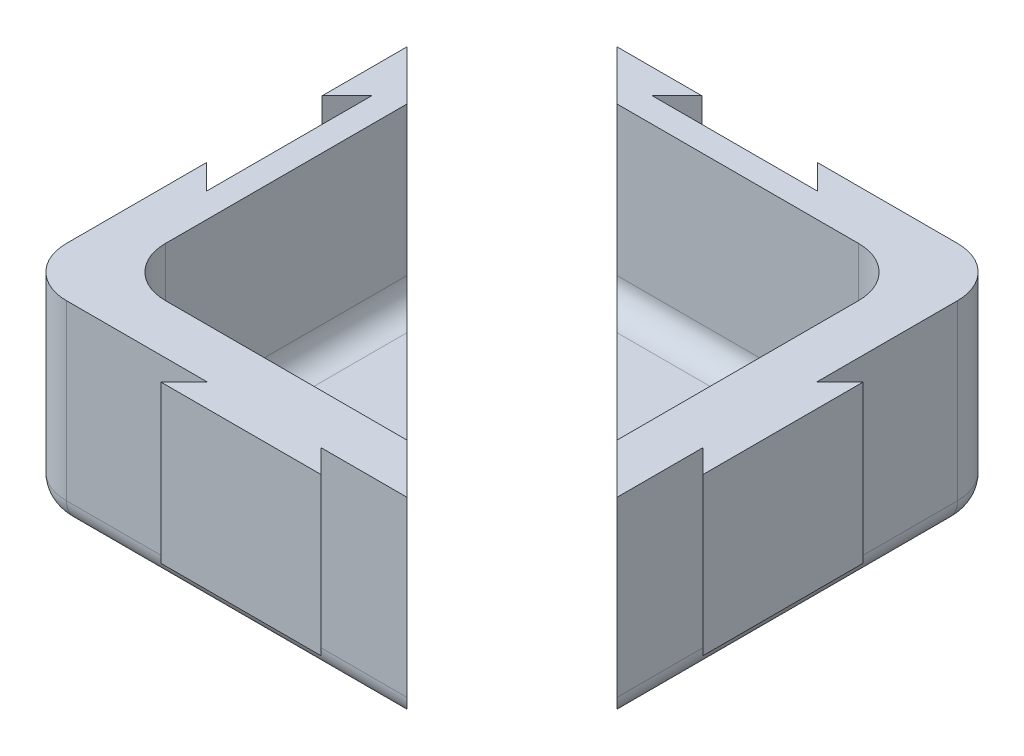
SolidWorks part; units mm, degrees
ref_plane "Front Plane" through (0, 0, 0) normal (0, 0, 1) x (1, 0, 0)
ref_plane "Top Plane" through (0, 0, 0) normal (0, 1, 0) x (1, 0, 0)
ref_plane "Right Plane" through (0, 0, 0) normal (1, 0, 0) x (0, 0, -1)
sketch "Sketch1" plane through (0, 0, 0) normal (0, 1, 0) x (1, 0, 0)
  line L1 (-50, 50) -> (50, 50)
  line L2 (-50, 50) -> (-50, -50)
  line L3 (-50, -50) -> (50, -50)
  line L4 (50, 50) -> (50, -50)
  line L5 (-50, 50) -> (50, -50) construction
  line L6 (-50, -50) -> (50, 50) construction
  point P0 (0, 0)
  dimension "D1" = 100
  dimension "D2" = 100
extrude "Boss-Extrude1" add sketch "Sketch1" along normal blind 40
shell "Shell1" thickness 10
sketch "Sketch2" plane through (0, 40, 0) normal (0, 1, 0) x (1, 0, 0)
  line L0 (-50, 45) -> (50, 45) construction
  line L1 (-50, 50) -> (-50, -50) construction
  line L2 (50, -50) -> (50, 50) construction
  line L3 (40, 40) -> (-40, 40) construction
  line L4 (-11.6667, 50) -> (-16.6667, 45)
  line L5 (50, 50) -> (-50, 50) construction
  line L6 (-16.6667, 45) -> (16.6667, 45)
  line L7 (16.6667, 45) -> (11.6667, 50)
  line L8 (-11.6667, 50) -> (11.6667, 50)
  point P14 (0, 45)
  dimension "D1" = 5
  dimension "D2" = 45
  dimension "D3" = 100
  dimension "D4" = 33.3333
extrude "Cut-Extrude1" cut sketch "Sketch2" against normal blind 32
sketch "Sketch3" plane through (0, 40, 0) normal (0, 1, 0) x (1, 0, 0)
  line L0 (-11.6667, -50) -> (-16.6667, -55) construction
  line L1 (-50, -50) -> (50, -50) construction
  line L2 (-16.6667, -55) -> (16.6667, -55) construction
  line L3 (16.6667, -55) -> (11.6667, -50) construction
  line L4 (11.6667, -50) -> (-11.6667, -50) construction
  line L5 (-50, -45) -> (50, -45) construction
  line L6 (-50, 50) -> (-50, -50) construction
  line L7 (50, -50) -> (50, 50) construction
  line L8 (-40, -40) -> (40, -40) construction
  line L9 (-11.4545, -50) -> (-16.1545, -54.7)
  line L10 (-11.4545, -50) -> (11.4545, -50)
  line L11 (-16.1545, -54.7) -> (16.1545, -54.7)
  line L12 (-11.5606, -50.1061) -> (-16.5606, -55.1061) construction
  line L14 (16.1545, -54.7) -> (11.4545, -50)
  point P4 (0, -50)
  dimension "D3" = 100
  dimension "D4" = 33.3333
  dimension "D1" = 45
  dimension "D2" = 5
  dimension "D5" = 5
  dimension "D7" = 0.3
  dimension "D8" = 0.15
  dimension "D6" = 0.15
extrude "Boss-Extrude2" add sketch "Sketch3" against normal blind 31.7
sketch "Sketch4" plane through (0, 40, 0) normal (0, 1, 0) x (1, 0, 0)
  line L0 (-45, 50) -> (-45, -50) construction
  line L1 (-11.6667, 50) -> (-50, 50) construction
  line L2 (-50, -50) -> (-11.4545, -50) construction
  line L3 (-40, 40) -> (-40, -40) construction
  line L4 (-45, 16.6667) -> (-45, -16.6667)
  line L5 (-45, -16.6667) -> (-50, -11.6667)
  line L6 (-50, 50) -> (-50, -50) construction
  line L7 (-50, -11.6667) -> (-50, 11.6667)
  line L8 (-50, 11.6667) -> (-45, 16.6667)
  point P14 (-45, 0)
  dimension "D1" = 5
  dimension "D2" = 45
  dimension "D3" = 33.3333
extrude "Cut-Extrude2" cut sketch "Sketch4" against normal blind 32
sketch "Sketch5" plane through (0, 40, 0) normal (0, 1, 0) x (1, 0, 0)
  line L0 (50, 11.6667) -> (50, -11.6667) construction
  line L1 (50, -50) -> (50, 50) construction
  line L2 (50, -11.6667) -> (55, -16.6667) construction
  line L3 (55, -16.6667) -> (55, 16.6667) construction
  line L4 (55, 16.6667) -> (50, 11.6667) construction
  line L5 (45, 50) -> (45, -50) construction
  line L6 (50, 50) -> (11.6667, 50) construction
  line L7 (11.4545, -50) -> (50, -50) construction
  line L8 (50, 11.4545) -> (50, -11.4545)
  line L9 (40, -40) -> (40, 40) construction
  line L10 (50, -11.4545) -> (54.7, -16.1545)
  line L12 (54.7, -16.1545) -> (54.7, 16.1545)
  line L13 (54.7, -16.6667) -> (54.7, 16.6667) construction
  line L14 (54.7, 16.1545) -> (50, 11.4545)
  line L15 (50.1061, -11.5606) -> (55.1061, -16.5606) construction
  point P14 (50, 0)
  dimension "D1" = 5
  dimension "D2" = 45
  dimension "D4" = 33.3333
  dimension "D3" = 5
  dimension "D7" = 0.15
  dimension "D5" = 0.15
  dimension "D6" = 0.3
extrude "Boss-Extrude3" add sketch "Sketch5" against normal up to surface (31.7 mm away) up to face at (0, 8.3, 52.35)
fillet "Fillet1" radius 10 8 edges at (40, 22.5, 40) (50, 20, 50) (50, 20, -50) (40, 22.5, -40) (-40, 22.5, -40) (-50, 20, -50) (-40, 22.5, 40) (-50, 20, 50)
fillet "Fillet2" radius 5 16 edges at (-47.0711, 0, -47.0711) (-50, 0, 0) (-47.0711, 0, 47.0711) (0, 0, 50) (47.0711, 0, 47.0711) (50, 0, 0) (47.0711, 0, -47.0711) (0, 0, -50) (37.0711, 5, 37.0711) (0, 5, 40) (-37.0711, 5, 37.0711) (-40, 5, 0) (-37.0711, 5, -37.0711) (0, 5, -40) (37.0711, 5, -37.0711) (40, 5, 0)
sketch "Sketch6" plane through (0, 40, 0) normal (0, 1, 0) x (1, 0, 0)
  line L0 (-47.0711, 47.0711) -> (47.0711, -47.0711)
  arc A0 (-40, 50) -> (-50, 40) centre (-40, 40) ccw construction
  arc A1 (40, -50) -> (50, -40) centre (40, -40) ccw construction
extrude "Cut-Extrude-Thin1" cut sketch "Sketch6" against normal through all both and the other way through all thin thin type mid plane wall 30
equation "\"x\" = 100"
equation "\"y\"= 100"
equation "\"h\"= 40"
equation "\"D1@Sketch1\"=\"x\""
equation "\"D2@Sketch1\"=\"y\""
equation "\"D4@Sketch2\"=\"x\"/3"
equation "\"D1@Cut-Extrude1\"=\"h\"*0.8"
equation "\"D5@Sketch3\"=\"D2@Sketch3\""
equation "\"Tolerance\"= 0.15"
equation "\"D6@Sketch3\"=\"Tolerance\""
equation "\"D7@Sketch3\"=\"Tolerance\"*2"
equation "\"D8@Sketch3\"=\"Tolerance\""
equation "\"D1@Boss-Extrude2\"=\"h\"*0.8 - (\"Tolerance\" * 2)"
equation "\"D4@Sketch3\"=\"x\"/3"
equation "\"D3@Sketch4\"=\"y\"/3"
equation "\"D1@Cut-Extrude2\"=\"h\"*0.8"
equation "\"D3@Sketch5\"=\"D1@Sketch5\""
equation "\"D4@Sketch5\"=\"y\"/3"
equation "\"D6@Sketch5\"=\"Tolerance\"*2"
equation "\"D5@Sketch5\"=\"Tolerance\""
equation "\"D7@Sketch5\"=\"Tolerance\""
equation "\"D1@Boss-Extrude1\"=\"h\""
